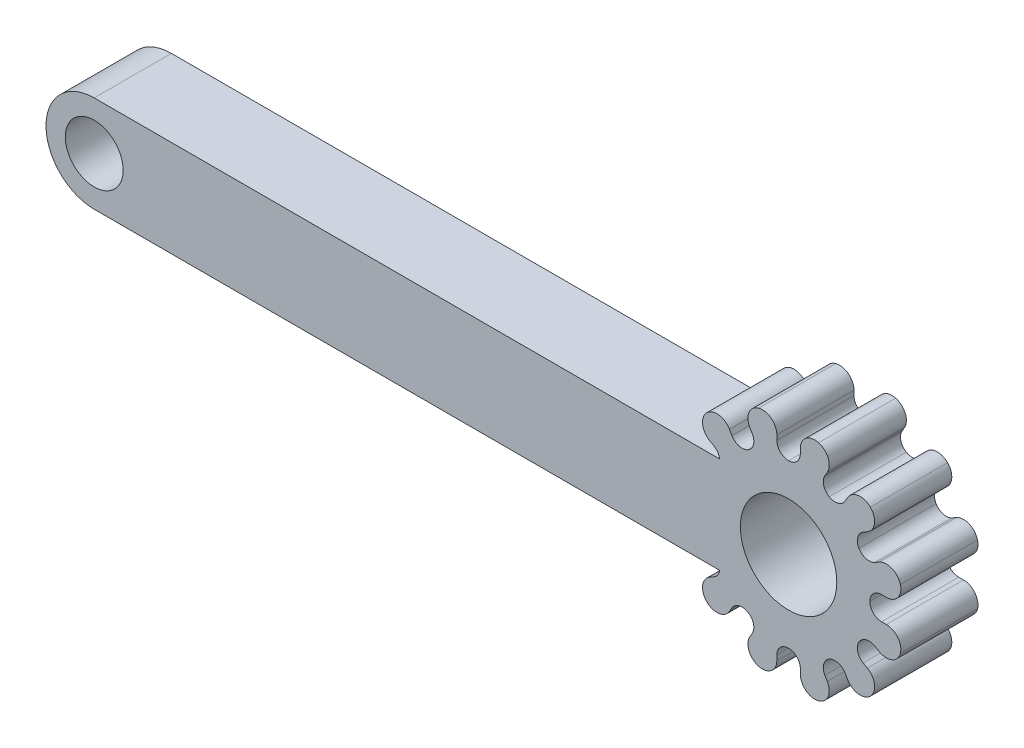
SolidWorks part; units mm, degrees
ref_plane "Front Plane" through (0, 0, 0) normal (0, 0, 1) x (1, 0, 0)
ref_plane "Top Plane" through (0, 0, 0) normal (0, 1, 0) x (1, 0, 0)
ref_plane "Right Plane" through (0, 0, 0) normal (1, 0, 0) x (0, 0, -1)
sketch "Sketch1" plane through (0, 0, 0) normal (0, 0, 1) x (1, 0, 0)
  line L0 (18, 0) -> (-18, 0) construction
  line L1 (-18, 2.5) -> (12.5456, 2.5)
  line L2 (-18, -2.5) -> (12.5456, -2.5)
  arc A0 (-18, 2.5) -> (-18, -2.5) centre (-18, 0) ccw
  circle A1 centre (-18, 0) radius 1.5
  arc A2 (12.5456, -2.5) -> (12.5456, 2.5) centre (18, 0) ccw
  point P4 (0, 0)
  dimension "D2" = 12
  dimension "D3" = 3
  dimension "D4" = 5
  dimension "D1" = 36
extrude "Boss-Extrude1" add sketch "Sketch1" along normal blind 4
sketch "Sketch2" plane through (0, 0, 4) normal (0, 0, 1) x (1, 0, 0)
  line L0 (18, 6) -> (18, -6) construction
  line L1 (18, 0) -> (22.2426, 4.2426) construction
  line L2 (18, 0) -> (19.5529, 5.7956) construction
  line L4 (18, 0) -> (20.105, 3.646) construction
  line L6 (20.0081, 4.6956) -> (19.8829, 4.4792)
  line L7 (21.0624, 4.0868) -> (20.9376, 3.8702)
  arc A0 (19.5529, 5.7956) -> (22.2426, 4.2426) centre (19.724, 2.9861) cw
  arc A8 (12.5456, -2.5) -> (12.5456, 2.5) centre (18, 0) ccw construction
  arc A9 (19.5529, 5.7956) -> (20.0081, 4.6956) centre (19.3589, 5.0711) cw
  arc A10 (19.8829, 4.4792) -> (20.105, 3.646) centre (20.4109, 4.1737) ccw
  arc A11 (20.9376, 3.8702) -> (20.105, 3.646) centre (20.4091, 4.1748) cw
  arc A12 (22.2426, 4.2426) -> (21.0624, 4.0868) centre (21.7123, 3.7124) ccw
  dimension "D4" = 15
  dimension "D6" = 1.1
  dimension "D7" = 0.25
  dimension "D5" = 0.75
  dimension "D8" = 0.61
  dimension "D1" = 15
  dimension "D2" = 30
  dimension "D3" = 4.21
extrude "Cut-Extrude1" cut sketch "Sketch2" against normal through all
pattern_circular "CirPattern1" count 12 over 360 about axis through (18, 0, 0) along (0, 0, 1) of "Cut-Extrude1"
sketch "Sketch3" plane through (0, 0, 4) normal (0, 0, 1) x (1, 0, 0)
  line L0 (12.3083, 2.5) -> (-18, 2.5) construction
  line L1 (10.2871, 2.5) -> (16.2777, 2.5)
  line L2 (10.2871, 2.5) -> (10.2871, -2.5)
  line L3 (10.2871, -2.5) -> (16.2777, -2.5)
  line L4 (16.2777, 2.5) -> (16.2777, -2.5)
  line L5 (-18, -2.5) -> (12.3083, -2.5) construction
extrude "Boss-Extrude2" add sketch "Sketch3" against normal blind 4
sketch "Sketch4" plane through (0, 0, 4) normal (0, 0, 1) x (1, 0, 0)
  line L0 (18, 6) -> (18, -6) construction
  circle A0 centre (18, 0) radius 2.5
  point P6 (0, 0)
  point P7 (18, 0)
  point P8 (0, 0)
  dimension "D1" = 5
extrude "Cut-Extrude2" cut sketch "Sketch4" against normal through all
